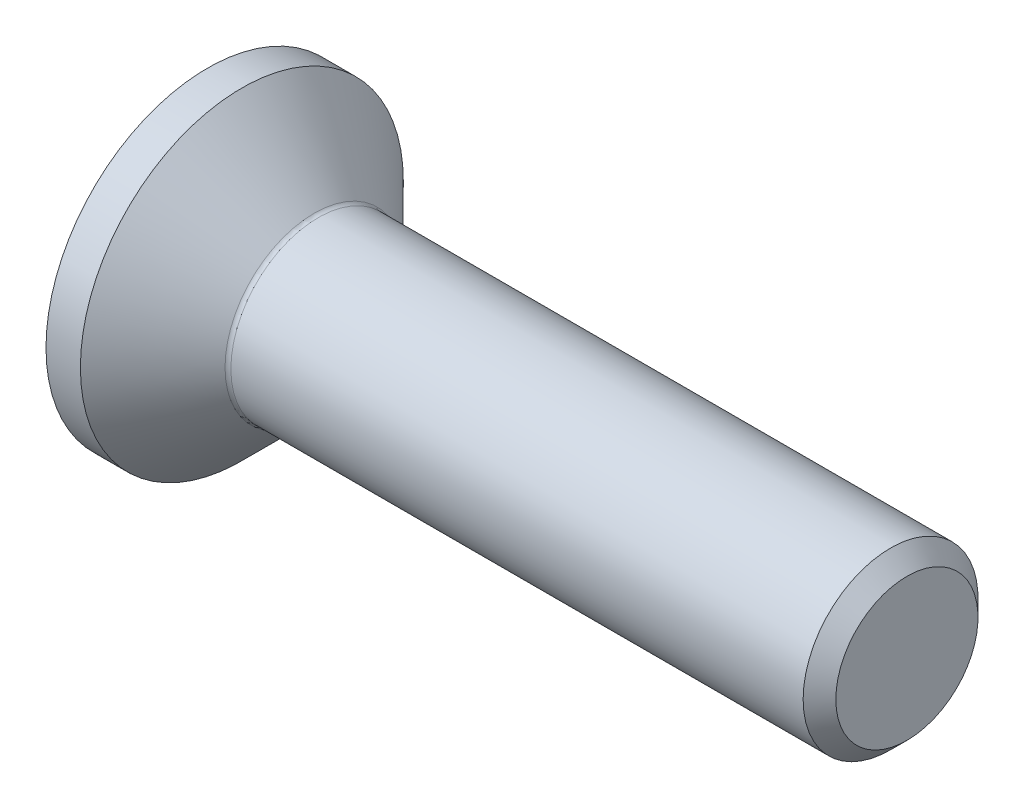
SolidWorks part; units mm, degrees
ref_plane "Plane1" through (0, 0, 0) normal (0, 0, 1) x (1, 0, 0)
ref_plane "Plane2" through (0, 0, 0) normal (0, 1, 0) x (1, 0, 0)
ref_plane "Plane3" through (0, 0, 0) normal (1, 0, 0) x (0, 0, -1)
sketch "BodySke" plane through (0, 0, 0) normal (0, 0, 1) x (1, 0, 0)
  line L0 (0, 0) -> (0, 2.77)
  line L1 (0.59, 2.77) -> (1.86, 1.5)
  line L2 (0, 2.77) -> (0.59, 2.77)
  line L3 (1.86, 1.5) -> (11.7195, 1.5)
  line L4 (12, 1.2195) -> (12, 0)
  line L5 (12, 0) -> (0, 0)
  line L6 (0, 0) -> (127, 0) construction
  line L7 (0.59, -2.77) -> (1.86, -1.5) construction
  line L8 (12, 1.2195) -> (11.7195, 1.5)
  line L9 (0, -2.77) -> (0.59, -2.77) construction
  line L10 (12, -1.2195) -> (11.7195, -1.5) construction
  line L11 (2.36, 7.85) -> (2.36, -14.375) construction
  line L12 (0, 19.05) -> (0, -3.175) construction
  dimension "D1" = 0.59
  dimension "Diameter" = 3
  dimension "Head_ht" = 1.86
  dimension "Length" = 12
  dimension "Body_ch_ang" = 45
  dimension "Head_dia" = 5.54
  dimension "Minor_dia" = 2.439
  dimension "Head_ang" = 90
  dimension "Advance" = 0.5
  dimension "Thread_nom" = 12
revolve "BaseBody" add sketch "BodySke"
cosmetic thread "ThreadCosmetic" [suppressed]
fillet "Fillet1" radius 0.1 1 edges at (1.86, 0, 1.5)
sketch "Sketch2" plane through (0, 0, 0) normal (0, 0, 1) x (1, 0, 0)
  line L0 (0, 1) -> (1.1, 1)
  line L1 (1.1, 1) -> (1.6774, 0)
  line L2 (0, 0) -> (127, 0) construction
  line L3 (1.6774, 0) -> (0, 0)
  line L4 (0, 0) -> (0, 1)
  line L5 (0, -1) -> (1.1, -1) construction
  line L6 (0, 0) -> (47.625, 0) construction
  line L8 (0, 2.77) -> (0, -2.77) construction
  dimension "D2" = 60
  dimension "PreBroach_depth" = 1.1
  dimension "PreBroach_dia" = 2
revolve "PreBroach" cut sketch "Sketch2" angle 360 about L6
sketch "Sketch3" plane through (0, 0, 0) normal (-1, 0, 0) x (0, 0, 1)
  line L0 (-1, -0.5774) -> (-1, 0.5774)
  line L1 (-1, 0.5774) -> (0, 1.1547)
  line L2 (0, 1.1547) -> (1, 0.5774)
  line L3 (1, 0.5774) -> (1, -0.5774)
  line L4 (1, -0.5774) -> (0, -1.1547)
  line L5 (0, -1.1547) -> (-1, -0.5774)
  dimension "D1" = 1
  dimension "D2" = 1
  dimension "D3" = 2
  dimension "Hex_size" = 2
extrude "Hex" cut sketch "Sketch3" against normal blind 1.1
sketch "ThdSchSke" plane through (0, 0, 0) normal (0, 0, 1) x (1, 0, 0)
  line L0 (3.36, -1.2195) -> (3.1636, -1.5)
  line L1 (3.36, -1.2195) -> (3.5564, -1.5)
  line L2 (3.5564, -1.5) -> (3.5564, -1.875)
  line L3 (-3.175, 0) -> (5.1513, 0) construction
  line L4 (0, 2.77) -> (0, -2.77) construction
  line L5 (3.5564, -1.875) -> (3.1636, -1.875)
  line L6 (3.1636, -1.875) -> (3.1636, -1.5)
  dimension "Thread_minor" = 2.439
  dimension "Diameter" = 3
  dimension "Start" = 3.36
  dimension "SideAngle" = 55
  dimension "VeeAngle" = 70
  dimension "Overcut" = 3.75
revolve "ThreadSchematic" [suppressed] cut sketch "ThdSchSke" angle 360 about L3
pattern_linear "ThdSchPat" [suppressed]
equation "\"Thread_minor@ThreadCosmetic\"  =  \"Minor_dia@BodySke\""
equation "\"D1@Sketch3\" = \"Hex_size@Sketch3\" / 2"
equation "\"D2@Sketch3\" = \"D1@Sketch3\""
equation "\"D3@Sketch3\" = \"Hex_size@Sketch3\""
equation "\"Thread_length@ThreadCosmetic\" = ((sgn( (\"Length@BodySke\" - \"Advance@BodySke\" * 3.0 - \"Head_ht@BodySke\" ) - \"Thread_nom@BodySke\" )-1)*( (\"Length@BodySke\" - \"Advance@BodySke\" * 3.0 - \"Head_ht@BodySke\" ) - \"Thread_nom@BodySke\" ))/-2+ \"Thread_nom@BodySke\""
equation "\"Thread_minor@ThdSchSke\" = \"Minor_dia@BodySke\""
equation "\"Diameter@ThdSchSke\" = \"Diameter@BodySke\""
equation "\"Overcut@ThdSchSke\" = \"Diameter@BodySke\" * 1.25"
equation "\"Start@ThdSchSke\" = 0.000001 + \"Length@BodySke\" - \"Thread_length@ThreadCosmetic\"  '---Countersunk---"
equation "\"Num_threads@ThdSchPat\" = int( \"Thread_length@ThreadCosmetic\" / \"Advance@BodySke\" + 0.999 )  + 1"
equation "\"Advance@ThdSchPat\" = \"Thread_length@ThreadCosmetic\" /  (\"Num_threads@ThdSchPat\" - 1) 'relax it"
equation "\"Num_threads@ThdSchPat\" = \"Num_threads@ThdSchPat\" - sgn( \"Num_threads@ThdSchPat\" - 1) '---chamfered tips only---"
